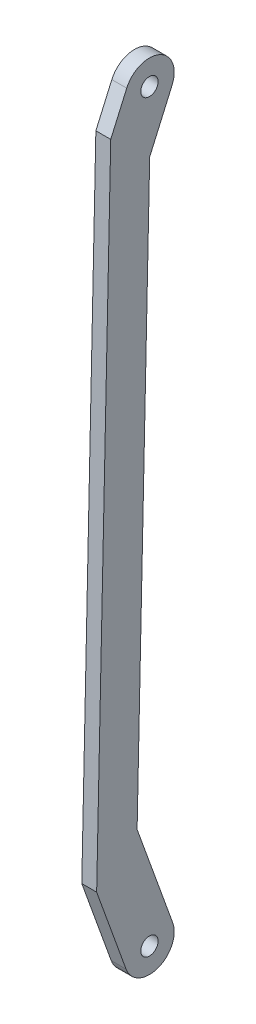
SolidWorks part; units mm, degrees
ref_plane "Alzado" through (0, 0, 0) normal (0, 0, 1) x (1, 0, 0)
ref_plane "Planta" through (0, 0, 0) normal (0, 1, 0) x (1, 0, 0)
ref_plane "Vista lateral" through (0, 0, 0) normal (1, 0, 0) x (0, 0, -1)
sketch "Croquis1" plane through (0, 0, 0) normal (1, 0, 0) x (0, 0, -1)
  line L0 (4.7031, 1.7937) -> (-2.4827, 21.673)
  line L1 (-4.5766, 152.1055) -> (4.5784, 148.0824) construction
  line L2 (-10.6345, 14.8083) -> (-7.7959, 144.7795)
  line L3 (4.7031, 1.7937) -> (-4.7013, -1.6058) construction
  line L4 (-4.5766, 152.1055) -> (-7.7959, 144.7795)
  line L5 (-3.2176, 142.7699) -> (0.0009, 150.0939) construction
  line L6 (-3.2176, 142.7699) -> (-6.0337, 13.8265) construction
  line L7 (-6.0337, 13.8265) -> (0.0009, 0.0939) construction
  line L8 (-2.4827, 21.673) -> (0.0532, 137.7847)
  line L9 (0.0532, 137.7847) -> (4.5784, 148.0824)
  line L11 (-4.7013, -1.6058) -> (-10.6345, 14.8083)
  arc A0 (-4.7013, -1.6058) -> (4.7031, 1.7937) centre (0.0009, 0.0939) ccw
  arc A1 (4.5784, 148.0824) -> (-4.5766, 152.1055) centre (0.0009, 150.0939) ccw
  circle A4 centre (0.0009, 150.0939) radius 1.75
  circle A5 centre (0.0009, 0.0939) radius 1.75
  dimension "D1" = 8
  dimension "D2" = 15
  dimension "D3" = 150
  dimension "D4" = 10
  dimension "D7" = 5
  dimension "D8" = 8
  dimension "D5" = 128.9434
  dimension "D6" = 3.2185
  dimension "D9" = 10
  dimension "D10" = 116.1116
extrude "Saliente-Extruir1" add sketch "Croquis1" along normal blind 3
